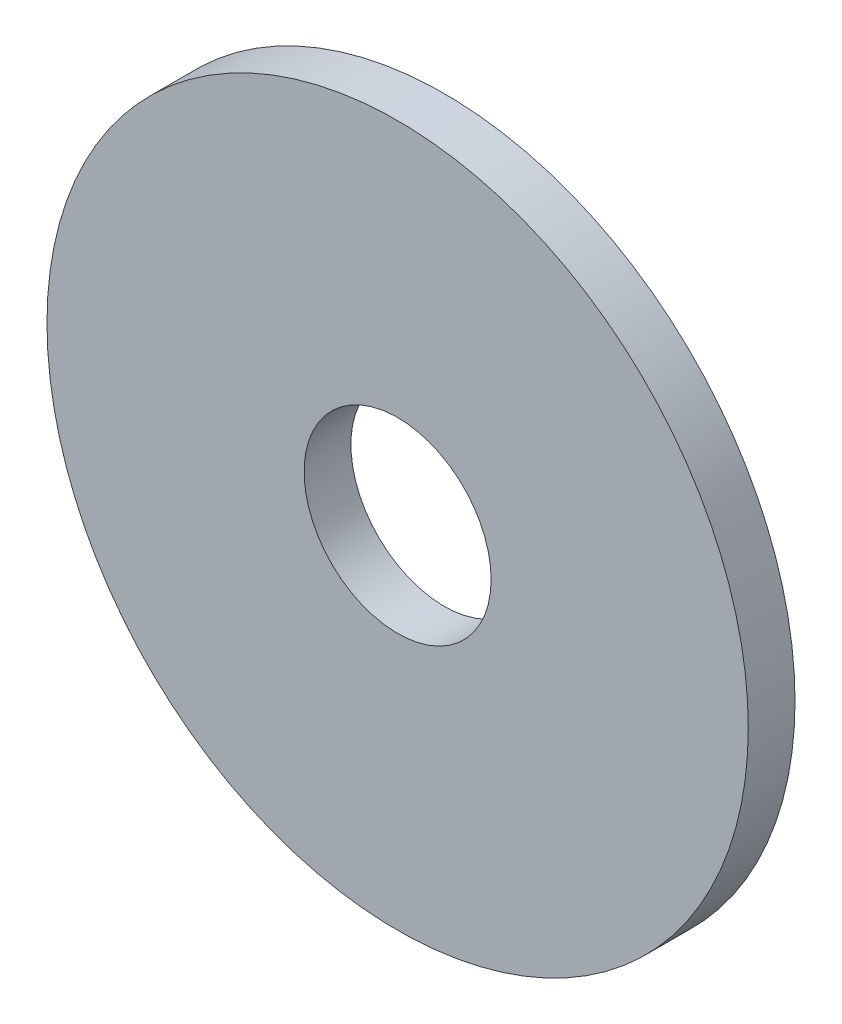
SolidWorks part; units mm, degrees
material "AISI 304"
ref_plane "Front" through (0, 0, 0) normal (0, 0, 1) x (1, 0, 0)
ref_plane "Top" through (0, 0, 0) normal (0, 1, 0) x (1, 0, 0)
ref_plane "Right" through (0, 0, 0) normal (1, 0, 0) x (0, 0, -1)
sketch "草图1" plane through (0, 0, 0) normal (0, 0, 1) x (1, 0, 0)
  circle A0 centre (0, 0) radius 2
  circle A1 centre (0, 0) radius 7.5
  dimension "D1" = 4
  dimension "D2" = 15
extrude "凸台-拉伸1" add sketch "草图1" along normal blind 1
